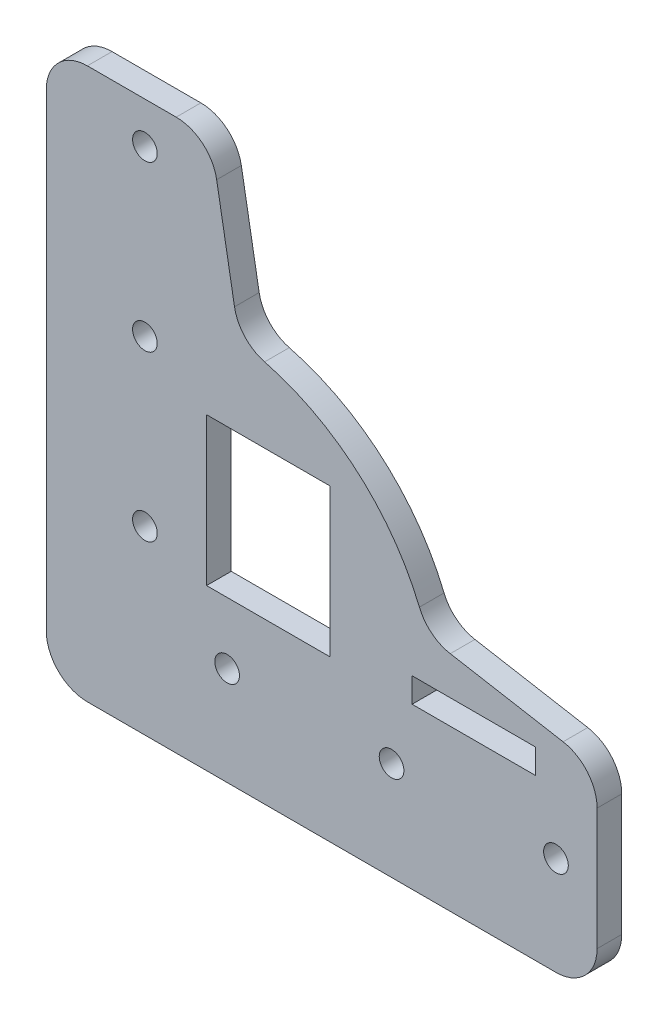
SolidWorks part; units mm, degrees
material "Thornel Mat VMA"
ref_plane "前视基准面" through (0, 0, 0) normal (0, 0, 1) x (1, 0, 0)
ref_plane "上视基准面" through (0, 0, 0) normal (0, 1, 0) x (1, 0, 0)
ref_plane "右视基准面" through (0, 0, 0) normal (1, 0, 0) x (0, 0, -1)
sketch "草图1" plane through (0, 0, 0) normal (0, 0, 1) x (1, 0, 0)
  line L0 (0, 0) -> (0, 67)
  line L1 (0, 67) -> (20, 67)
  line L2 (49.1428, 27.1487) -> (67, 24)
  line L3 (20, 67) -> (22.8979, 50.5652)
  line L4 (67, 24) -> (67, 0)
  line L5 (67, 0) -> (0, 0)
  line L6 (12, 67) -> (12, 12) construction
  line L7 (12, 12) -> (67, 12) construction
  line L9 (19.5, 37.5) -> (34.5, 37.5)
  line L10 (19.5, 37.5) -> (19.5, 19.5)
  line L11 (19.5, 19.5) -> (34.5, 19.5)
  line L12 (34.5, 37.5) -> (34.5, 19.5)
  line L13 (0, 0) -> (12, 12) construction
  line L16 (44.5, 19.5) -> (59.5, 19.5)
  line L17 (44.5, 19.5) -> (44.5, 22.5)
  line L18 (44.5, 22.5) -> (59.5, 22.5)
  line L19 (59.5, 19.5) -> (59.5, 22.5)
  circle A0 centre (12, 62) radius 1.5
  circle A1 centre (12, 42) radius 1.5
  circle A2 centre (12, 22) radius 1.5
  circle A3 centre (62, 12) radius 1.5
  circle A4 centre (42, 12) radius 1.5
  circle A5 centre (22, 12) radius 1.5
  arc A6 (26.561, 46.5951) -> (45.3882, 30.1678) centre (19.5, 19.5) cw
  arc A7 (45.3882, 30.1678) -> (49.1428, 27.1487) centre (50.0111, 32.0727) ccw
  arc A8 (22.8979, 50.5652) -> (26.561, 46.5951) centre (27.8219, 51.4335) ccw
  point P27 (44.5, 21)
  dimension "D14" = 3
  dimension "D16" = 20
  dimension "D17" = 20
  dimension "D18" = 20
  dimension "D8" = 28
  dimension "D9" = 5
  dimension "D2" = 12
  dimension "D3" = 12
  dimension "D4" = 7.5
  dimension "D5" = 18
  dimension "D6" = 67
  dimension "D7" = 67
  dimension "D10" = 10
  dimension "D11" = 24
  dimension "D12" = 10
  dimension "D13" = 15
  dimension "D15" = 10
  dimension "D19" = 10
  dimension "D20" = 15
  dimension "D21" = 3
  dimension "D22" = 7.5
extrude "凸台-拉伸1" add sketch "草图1" along normal blind 3
fillet "圆角1" radius 5 5 edges at (0, 0, 1.5) (67, 0, 1.5) (67, 24, 1.5) (0, 67, 1.5) (20, 67, 1.5)
